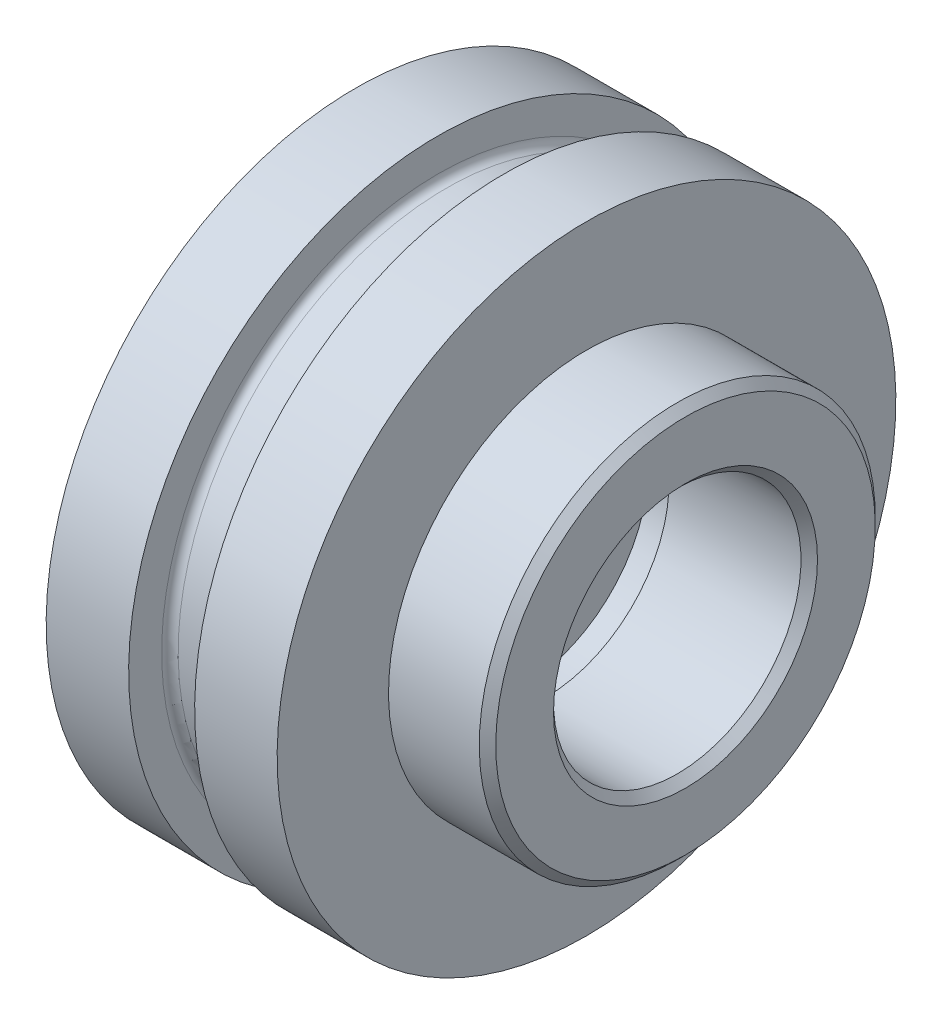
SolidWorks part; units mm, degrees
material "Алюминиевая бронза"
ref_plane "Спереди" through (0, 0, 0) normal (0, 0, 1) x (1, 0, 0)
ref_plane "Сверху" through (0, 0, 0) normal (0, 1, 0) x (1, 0, 0)
ref_plane "Справа" through (0, 0, 0) normal (1, 0, 0) x (0, 0, -1)
sketch "Эскиз1" plane through (0, 0, 0) normal (0, 0, 1) x (1, 0, 0)
  line L0 (2, 0) -> (58.1527, 0) construction
  line L1 (0, 34.5) -> (0, 37.5)
  line L2 (0, 37.5) -> (10, 37.5)
  line L3 (28, 37.5) -> (28, 24)
  line L4 (28, 24) -> (39, 24)
  line L5 (40, 23) -> (40, 16)
  line L6 (39, 15) -> (23, 15)
  line L7 (23, 15) -> (23, 15.5)
  line L8 (23, 15.5) -> (20, 15.5)
  line L9 (20, 15.5) -> (20, 0)
  line L10 (20, 0) -> (2, 0)
  line L11 (40, 16) -> (39, 15)
  line L12 (39, 24) -> (40, 23)
  line L13 (10, 37.5) -> (10, 33.5)
  line L14 (11, 32.5) -> (17, 32.5)
  line L15 (18, 33.5) -> (18, 37.5)
  line L16 (0, 34.5) -> (2, 34.5)
  line L17 (2, 34.5) -> (2, 0)
  line L18 (18, 37.5) -> (28, 37.5)
  arc A0 (17, 32.5) -> (18, 33.5) centre (17, 33.5) ccw
  arc A1 (10, 33.5) -> (11, 32.5) centre (11, 33.5) ccw
  point P0 (0, 36)
  point P7 (40, 24)
  point P8 (40, 15)
  point P26 (18, 32.5)
  point P29 (10, 32.5)
  dimension "D18" = 1
  dimension "D1" = 75
  dimension "D2" = 48
  dimension "D3" = 30
  dimension "D4" = 31
  dimension "D5" = 3
  dimension "D6" = 20
  dimension "D7" = 40
  dimension "D8" = 12
  dimension "D9" = 1
  dimension "D10" = 45
  dimension "D11" = 1
  dimension "D12" = 45
  dimension "D13" = 69
  dimension "D14" = 2
  dimension "D15" = 8
  dimension "D16" = 5
  dimension "D17" = 10
revolve "Повернуть1" add sketch "Эскиз1" angle 360 about L0
